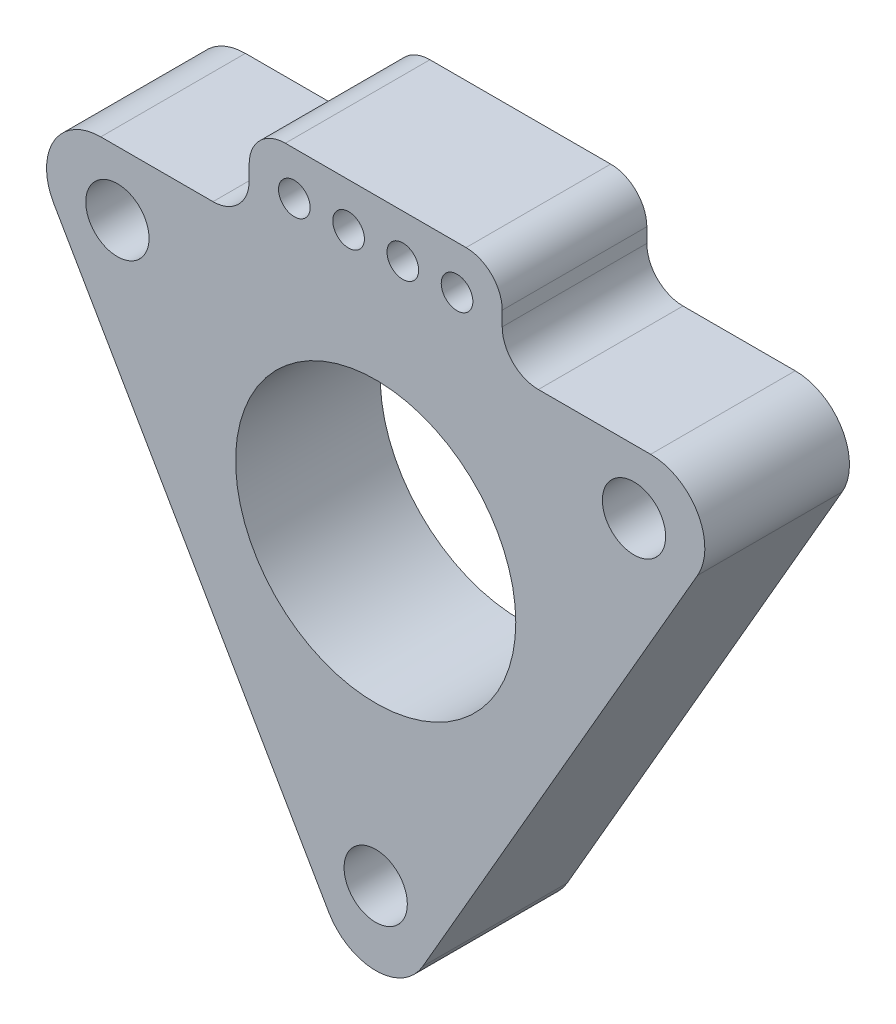
SolidWorks part; units mm, degrees
material "Bakelite"
ref_plane "Front Plane" through (0, 0, 0) normal (0, 0, 1) x (1, 0, 0)
ref_plane "Top Plane" through (0, 0, 0) normal (0, 1, 0) x (1, 0, 0)
ref_plane "Right Plane" through (0, 0, 0) normal (1, 0, 0) x (0, 0, -1)
sketch "Model" plane through (0, 0, 0) normal (0, 0, 1) x (1, 0, 0)
  line L0 (20.4053, 11.78) -> (-20.4053, 11.78)
  line L2 (0, -23.5631) -> (20.4053, 11.78)
  line L3 (-20.4053, 11.78) -> (0, -23.5631)
  circle A0 centre (0, -16.5) radius 1.75
  circle A1 centre (0, 0) radius 7.75
  circle A2 centre (-14.2894, 8.25) radius 1.75
  circle A3 centre (14.2894, 8.25) radius 1.75
  dimension "D1" = 15.5
  dimension "D2" = 3.5
  dimension "D3" = 11.7815
  dimension "D4" = 11.7815
  dimension "D5" = 11.78
  dimension "D6" = 60
  dimension "D13" = 16.5
extrude "Boss-Extrude1" add sketch "Model" along normal blind 8
fillet "Fillet1" radius 3 3 edges at (0, -23.5631, 4) (-20.4053, 11.78, 4) (20.4053, 11.78, 4)
sketch "Sketch1" plane through (0, 0, 0) normal (0, 0, -1) x (-1, 0, 0)
  line L0 (-7, 11.78) -> (-7, 16.58)
  line L1 (-15.2092, 11.78) -> (15.2092, 11.78) construction
  line L2 (-7, 16.58) -> (7, 16.58)
  line L3 (7, 16.58) -> (7, 11.78)
  line L4 (-7, 11.78) -> (7, 11.78)
  line L5 (0, 16.58) -> (0, 11.78) construction
  line L6 (-7, 14.18) -> (7, 14.18) construction
  circle A0 centre (-1.5, 14.18) radius 0.875
  circle A1 centre (-4.5, 14.18) radius 0.875
  circle A2 centre (1.5, 14.18) radius 0.875
  circle A3 centre (4.5, 14.18) radius 0.875
  point P4 (0, 11.78)
  point P7 (0, 11.78)
  dimension "D3" = 1.75
  dimension "D1" = 14
  dimension "D2" = 4.8
  dimension "D4" = 3
  dimension "D5" = 3
  dimension "D6" = 3
extrude "Boss-Extrude2" add sketch "Sketch1" against normal up to surface (8 mm away) up to face at (-12.5394, 8.25, 8)
fillet "Fillet2" radius 2 4 edges at (-7, 11.78, 4) (-7, 16.58, 4) (7, 16.58, 4) (7, 11.78, 4)
